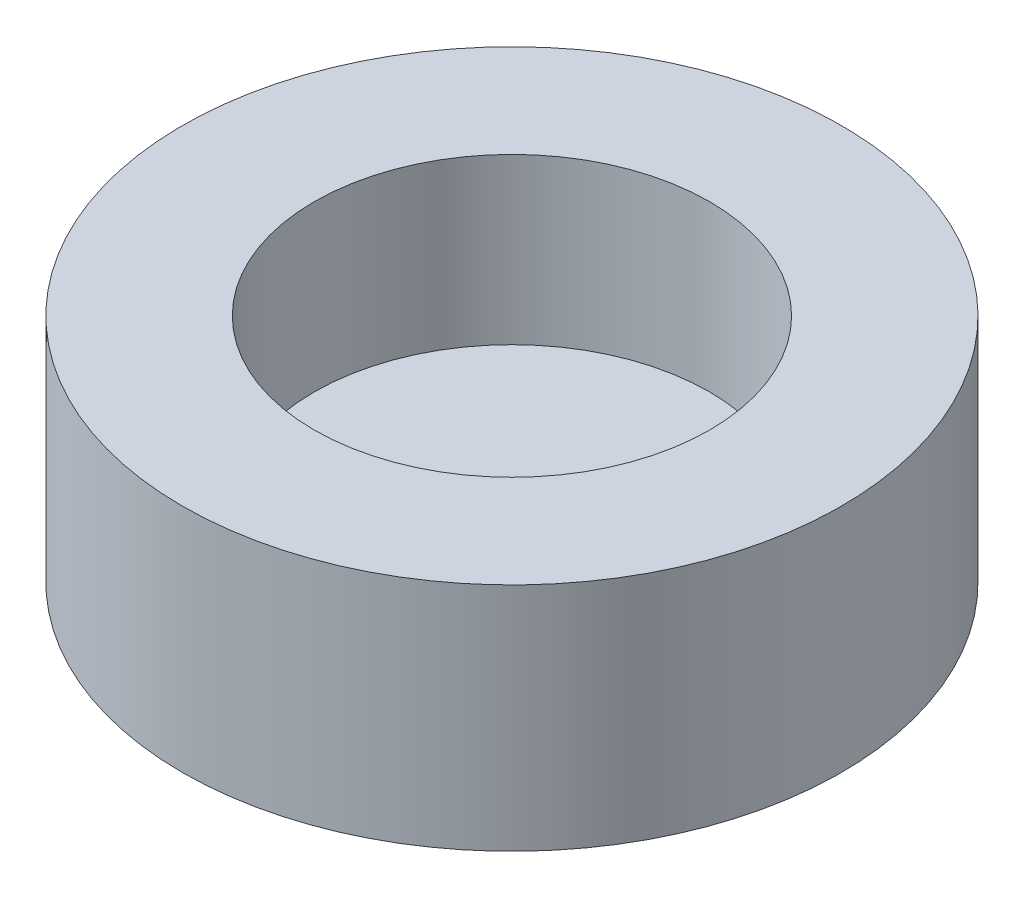
SolidWorks part; units mm, degrees
ref_plane "Ebene vorne" through (0, 0, 0) normal (0, 0, 1) x (1, 0, 0)
ref_plane "Ebene oben" through (0, 0, 0) normal (0, 1, 0) x (1, 0, 0)
ref_plane "Ebene rechts" through (0, 0, 0) normal (1, 0, 0) x (0, 0, -1)
sketch "Skizze1" plane through (0, 0, 0) normal (0, 1, 0) x (1, 0, 0)
  circle A0 centre (0, 0) radius 10
  dimension "D1" = 20
extrude "Aufsatz-Linear austragen1" add sketch "Skizze1" along normal blind 7
sketch "Skizze2" plane through (0, 7, 0) normal (0, 1, 0) x (1, 0, 0)
  circle A0 centre (0, 0) radius 6
  dimension "D1" = 12
extrude "Schnitt-Linear austragen1" cut sketch "Skizze2" against normal blind 5
